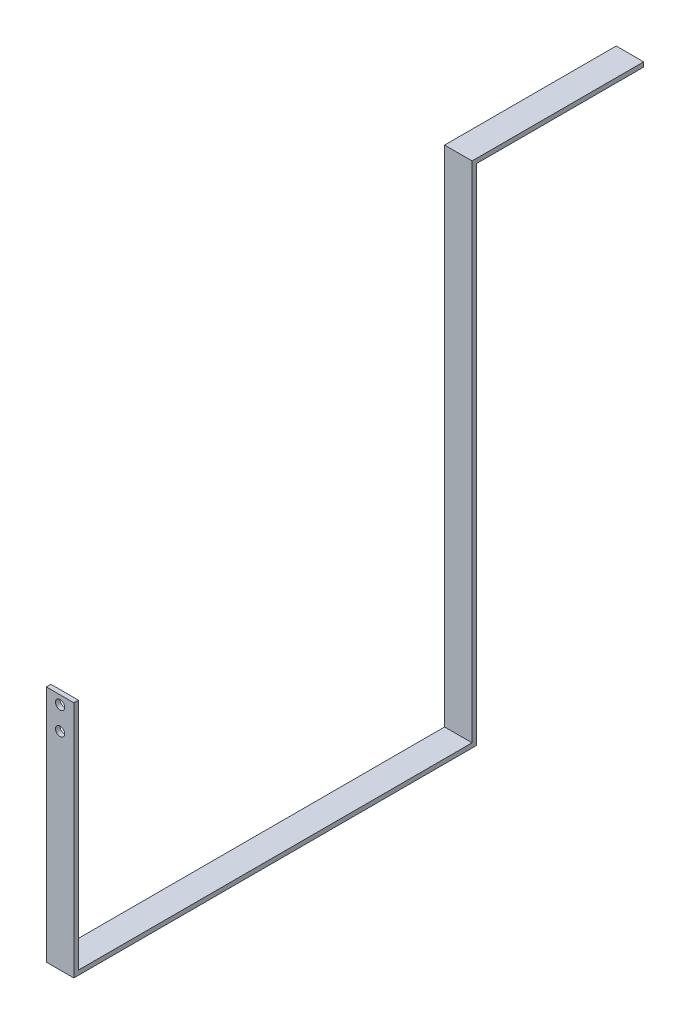
SolidWorks part; units mm, degrees
ref_plane "Alzado" through (0, 0, 0) normal (0, 0, 1) x (1, 0, 0)
ref_plane "Planta" through (0, 0, 0) normal (0, 1, 0) x (1, 0, 0)
ref_plane "Vista lateral" through (0, 0, 0) normal (1, 0, 0) x (0, 0, -1)
sketch "Croquis1" plane through (0, 0, 0) normal (0, 0, 1) x (1, 0, 0)
  line L1 (-19.05, -3.155) -> (19.05, -3.155)
  line L2 (-19.05, -3.155) -> (-19.05, 3.155)
  line L3 (-19.05, 3.155) -> (19.05, 3.155)
  line L4 (19.05, -3.155) -> (19.05, 3.155)
  line L5 (-19.05, -3.155) -> (19.05, 3.155) construction
  line L6 (-19.05, 3.155) -> (19.05, -3.155) construction
  point P0 (0, 0)
  dimension "D1" = 6.31
  dimension "D2" = 38.1
extrude "Saliente-Extruir1" add sketch "Croquis1" along normal blind 238.05
sketch "Croquis2" plane through (0, -3.155, 0) normal (0, -1, 0) x (1, 0, 0)
  line L0 (-19.05, 238.05) -> (19.05, 238.05)
  line L1 (19.05, 238.05) -> (19.05, 231.74)
  line L2 (19.05, 238.05) -> (19.05, 0) construction
  line L3 (19.05, 231.74) -> (-19.05, 231.74)
  line L4 (-19.05, 238.05) -> (-19.05, 0) construction
  line L5 (-19.05, 231.74) -> (-19.05, 238.05)
  dimension "D1" = 6.31
extrude "Saliente-Extruir2" add sketch "Croquis2" along normal blind 699.1
sketch "Croquis3" plane through (0, 0, 238.05) normal (0, 0, 1) x (1, 0, 0)
  line L0 (-19.05, -702.255) -> (19.05, -702.255)
  line L1 (19.05, -702.255) -> (19.05, -695.945)
  line L2 (19.05, -702.255) -> (19.05, 3.155) construction
  line L3 (19.05, -695.945) -> (-19.05, -695.945)
  line L4 (-19.05, 3.155) -> (-19.05, -702.255) construction
  line L5 (-19.05, -695.945) -> (-19.05, -702.255)
  dimension "D1" = 6.31
extrude "Saliente-Extruir3" add sketch "Croquis3" along normal blind 552.5
sketch "Croquis4" plane through (0, -695.945, 0) normal (0, 1, 0) x (1, 0, 0)
  line L0 (-19.05, -790.55) -> (19.05, -790.55)
  line L1 (19.05, -790.55) -> (19.05, -784.24)
  line L2 (19.05, -790.55) -> (19.05, -238.05) construction
  line L3 (19.05, -784.24) -> (-19.05, -784.24)
  line L4 (-19.05, -790.55) -> (-19.05, -238.05) construction
  line L5 (-19.05, -784.24) -> (-19.05, -790.55)
  dimension "D1" = 6.31
extrude "Saliente-Extruir4" add sketch "Croquis4" along normal blind 324.39
sketch "Croquis5" plane through (0, 0, 790.55) normal (0, 0, 1) x (1, 0, 0)
  line L0 (0, -383.4472) -> (0, -371.555) construction
  line L1 (-19.05, -371.555) -> (19.05, -371.555) construction
  line L2 (0, -383.4472) -> (0, -415.4472) construction
  line L3 (0, -415.4472) -> (21.1091, -415.4472) construction
  circle A0 centre (0, -383.4472) radius 6.35
  circle A1 centre (0, -415.4472) radius 6.35
extrude "Cortar-Extruir1" cut sketch "Croquis5" against normal blind 6.31
